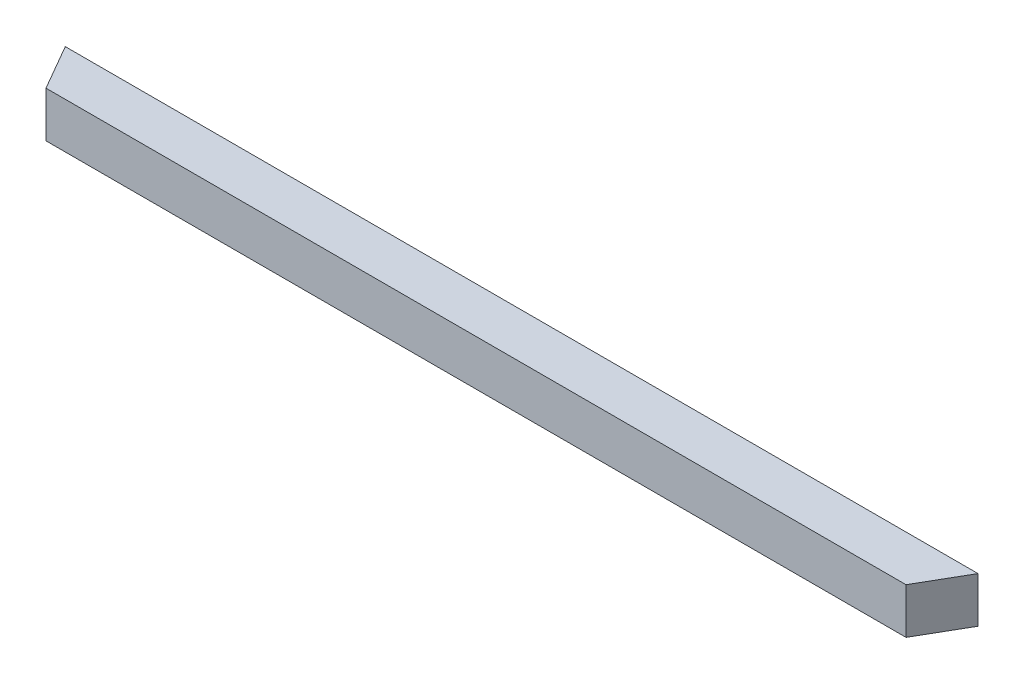
SolidWorks part; units mm, degrees
ref_plane "Front Plane" through (0, 0, 0) normal (0, 0, 1) x (1, 0, 0)
ref_plane "Top Plane" through (0, 0, 0) normal (0, 1, 0) x (1, 0, 0)
ref_plane "Right Plane" through (0, 0, 0) normal (1, 0, 0) x (0, 0, -1)
sketch "Sketch1" plane through (0, 0, 0) normal (0, 1, 0) x (1, 0, 0)
  line L0 (-200, 0) -> (200, 0)
  line L1 (-188.453, -20) -> (188.453, -20)
  line L2 (-200, 0) -> (-188.453, -20)
  line L3 (188.453, -20) -> (200, 0)
  point P4 (0, 0)
  point P7 (0, -20)
  dimension "D1" = 60
  dimension "D2" = 60
  dimension "D3" = 20
  dimension "D4" = 400
extrude "Boss-Extrude1" add sketch "Sketch1" along normal blind 20
